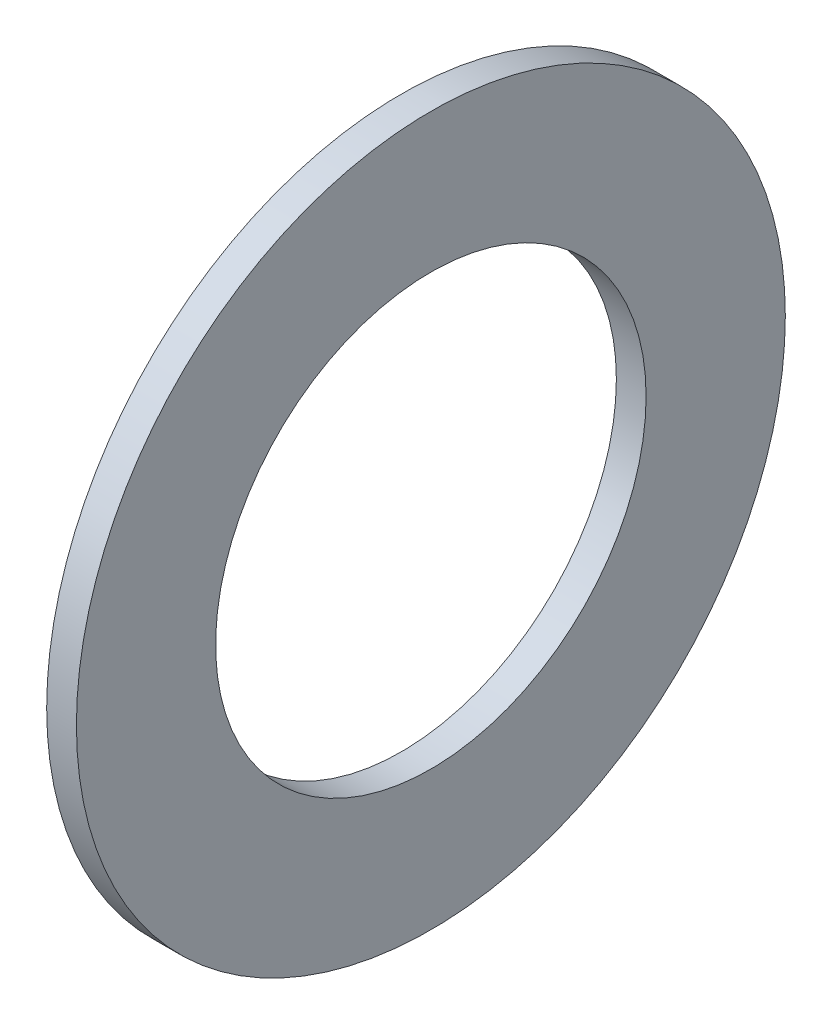
SolidWorks part; units mm, degrees
ref_plane "Ebene vorne" through (0, 0, 0) normal (0, 0, 1) x (1, 0, 0)
ref_plane "Ebene oben" through (0, 0, 0) normal (0, 1, 0) x (1, 0, 0)
ref_plane "Ebene rechts" through (0, 0, 0) normal (1, 0, 0) x (0, 0, -1)
sketch "Sketch1" plane through (0, 0, 0) normal (1, 0, 0) x (0, 0, -1)
  circle A0 centre (0, 0) radius 47.675
  circle A1 centre (0, 0) radius 28.95
  dimension "D1" = 95.35
  dimension "D2" = 57.9
extrude "Boss-Extrude1" add sketch "Sketch1" along normal blind 4
